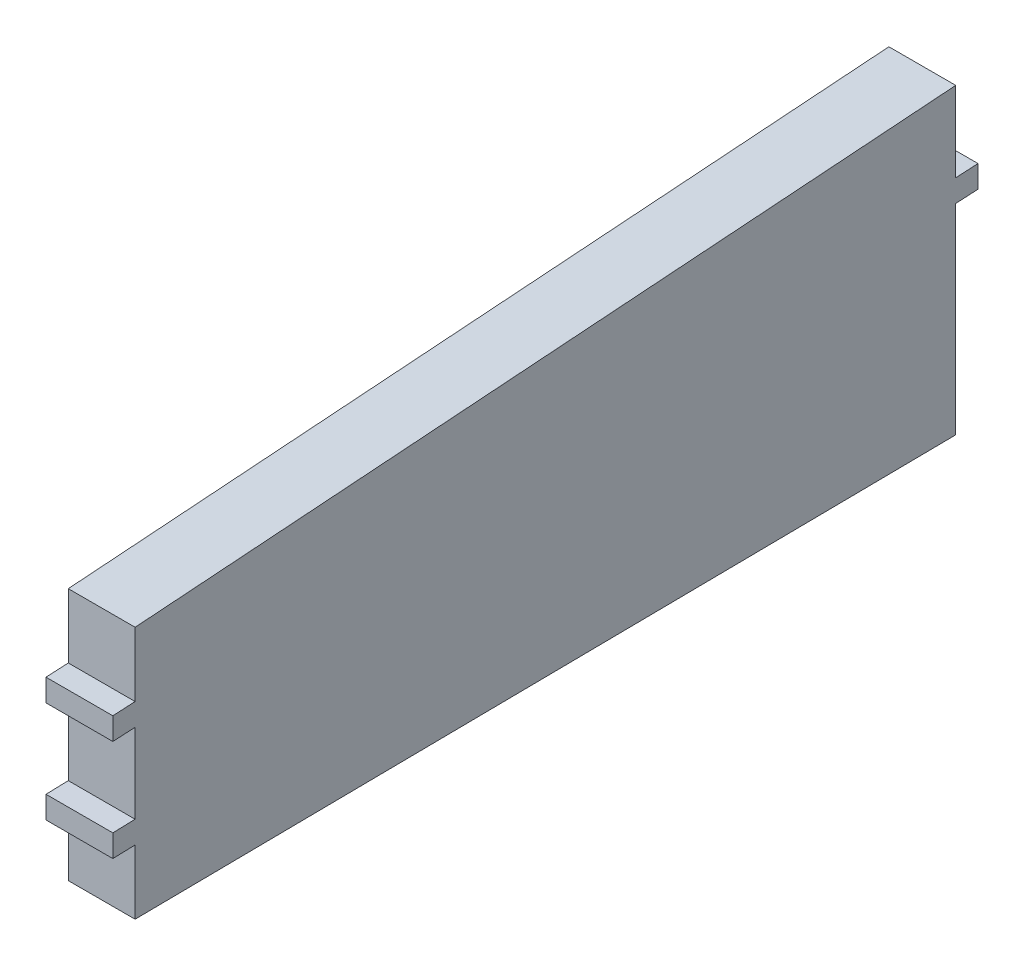
SolidWorks part; units mm, degrees
material "Balsa"
ref_plane "Front Plane" through (0, 0, 0) normal (0, 0, 1) x (1, 0, 0)
ref_plane "Top Plane" through (0, 0, 0) normal (0, 1, 0) x (1, 0, 0)
ref_plane "Right Plane" through (0, 0, 0) normal (1, 0, 0) x (0, 0, -1)
sketch "Sketch1" plane through (243.0177, 0, 0) normal (1, 0, 0) x (0, 0, -1)
  line L0 (-1140.4187, 370.1136) -> (-1140.4187, 366.9386) construction
  line L1 (-1140.4187, 366.9386) -> (-1137.2437, 367.0348) construction
  line L2 (-1137.2437, 384.7328) -> (-1140.4187, 384.5652) construction
  line L3 (-1137.2437, 370.2098) -> (-1140.4187, 370.1136) construction
  line L4 (-1140.4187, 384.5652) -> (-1140.4187, 381.3902) construction
  line L5 (-1020.2979, 387.7307) -> (-1017.1229, 387.8983) construction
  line L6 (-1017.1229, 387.8983) -> (-1017.1229, 391.0733) construction
  line L7 (-1017.1229, 391.0733) -> (-1020.2979, 390.9057) construction
  line L8 (-1137.2437, 357.8651) -> (-1140.4187, 357.8296) construction
  line L9 (-1137.2437, 393.9025) -> (-1140.4187, 393.6742) construction
  line L10 (-1017.1229, 359.2096) -> (-1020.2979, 359.174) construction
  line L11 (-1017.1229, 402.5385) -> (-1020.2979, 402.3102) construction
  line L12 (-1140.4187, 370.1136) -> (-1140.4187, 366.9386)
  line L13 (-1140.4187, 366.9386) -> (-1137.2437, 367.0348)
  line L15 (-1137.2437, 370.2098) -> (-1140.4187, 370.1136)
  line L17 (-1020.2979, 387.7307) -> (-1017.1229, 387.8983)
  line L18 (-1017.1229, 387.8983) -> (-1017.1229, 391.0733)
  line L19 (-1017.1229, 391.0733) -> (-1020.2979, 390.9057)
  line L20 (-1137.2437, 357.8651) -> (-1140.4187, 357.8296) construction
  line L21 (-1137.2437, 393.9025) -> (-1140.4187, 393.6742) construction
  line L22 (-1017.1229, 359.2096) -> (-1020.2979, 359.174) construction
  line L23 (-1017.1229, 402.5385) -> (-1020.2979, 402.3102) construction
  line L24 (-1020.2979, 402.3102) -> (-1137.2437, 393.9025)
  line L25 (-1137.2437, 393.9025) -> (-1137.2437, 384.7328)
  line L26 (-1137.2437, 367.0348) -> (-1137.2437, 357.8651)
  line L27 (-1137.2437, 357.8651) -> (-1020.2979, 359.174)
  line L28 (-1020.2979, 359.174) -> (-1020.2979, 387.7307)
  line L29 (-1020.2979, 390.9057) -> (-1020.2979, 402.3102)
  line L30 (-1137.2437, 381.5578) -> (-1140.4187, 381.3902) construction
  line L31 (-1137.2437, 384.7328) -> (-1140.4187, 384.5652)
  line L32 (-1140.4187, 384.5652) -> (-1140.4187, 381.3902)
  line L33 (-1137.2437, 381.5578) -> (-1140.4187, 381.3902)
  line L34 (-1137.2437, 381.5578) -> (-1137.2437, 370.2098)
extrude "Boss-Extrude1" add sketch "Sketch1" along normal up to surface (9.525 mm away)
